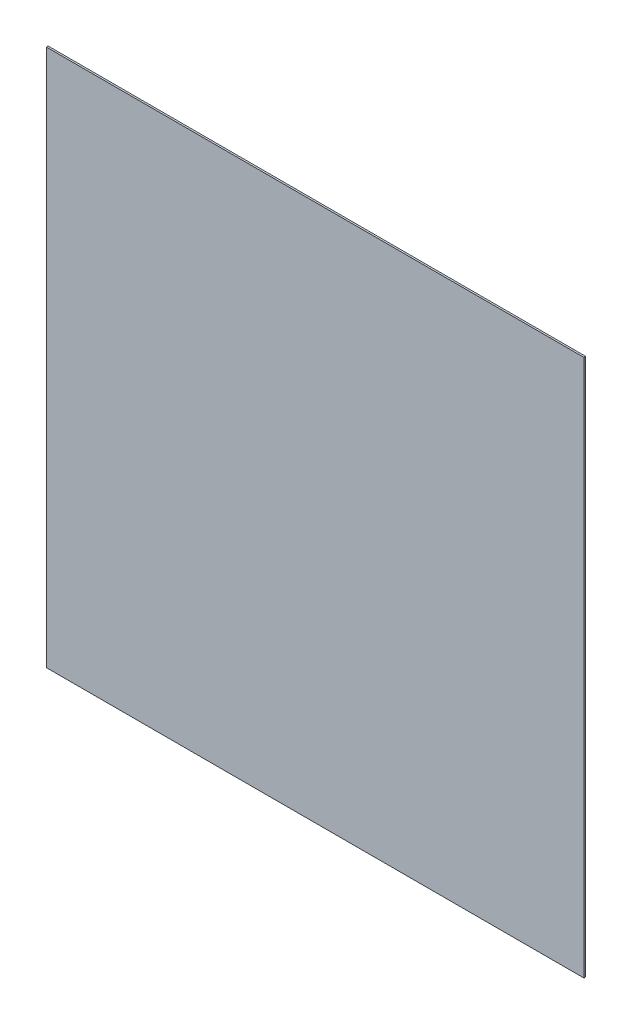
SolidWorks part; units mm, degrees
ref_plane "前视基准面" through (0, 0, 0) normal (0, 0, 1) x (1, 0, 0)
ref_plane "上视基准面" through (0, 0, 0) normal (0, 1, 0) x (1, 0, 0)
ref_plane "右视基准面" through (0, 0, 0) normal (1, 0, 0) x (0, 0, -1)
sketch "草图1" plane through (0, 0, 0) normal (0, 0, 1) x (1, 0, 0)
  line L1 (-150, -150) -> (150, -150)
  line L2 (-150, -150) -> (-150, 150)
  line L3 (-150, 150) -> (150, 150)
  line L4 (150, -150) -> (150, 150)
  line L5 (-150, -150) -> (150, 150) construction
  line L6 (-150, 150) -> (150, -150) construction
  point P0 (0, 0)
  dimension "D1" = 300
  dimension "D2" = 300
extrude "凸台-拉伸1" add sketch "草图1" along normal blind 1
